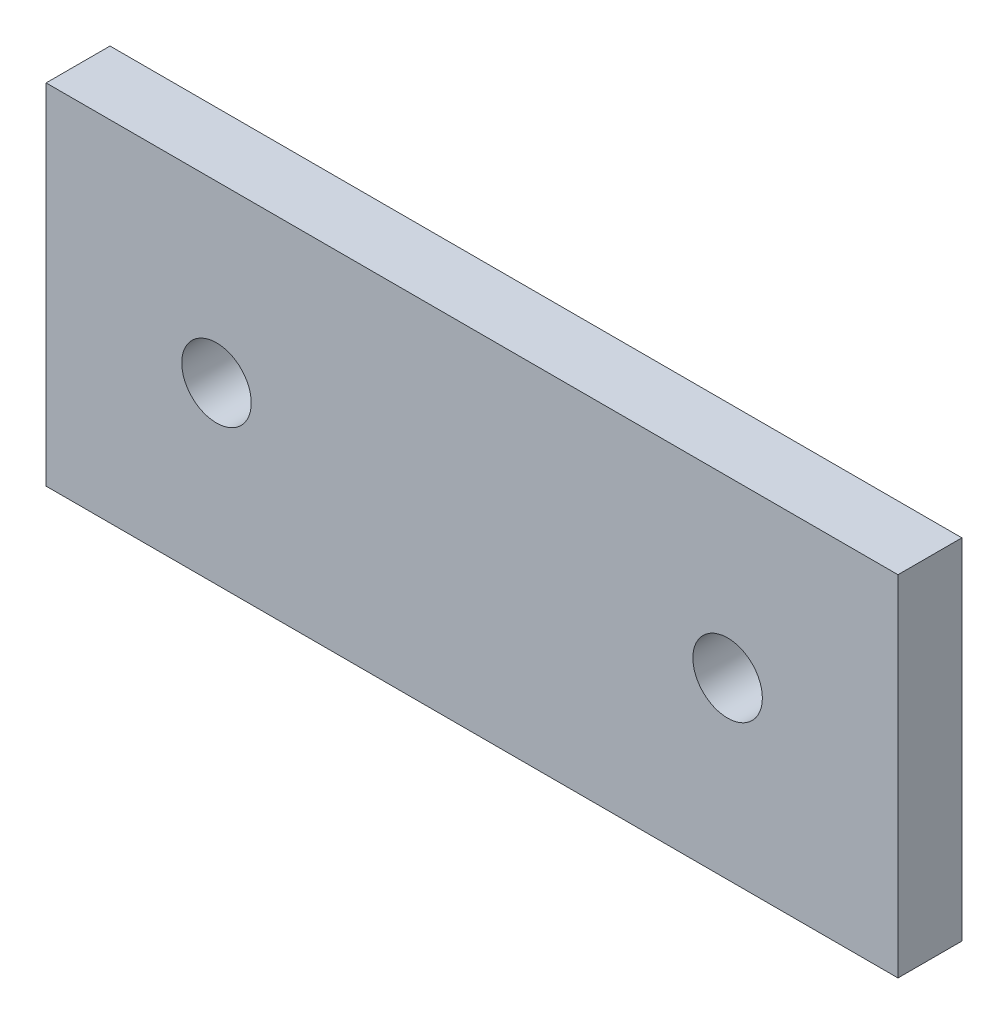
SolidWorks part; units mm, degrees
ref_plane "Front Plane" through (0, 0, 0) normal (0, 0, 1) x (1, 0, 0)
ref_plane "Top Plane" through (0, 0, 0) normal (0, 1, 0) x (1, 0, 0)
ref_plane "Right Plane" through (0, 0, 0) normal (1, 0, 0) x (0, 0, -1)
sketch "Sketch1" plane through (0, 0, 0) normal (0, 0, 1) x (1, 0, 0)
  line L1 (-20, 8.2) -> (20, 8.2)
  line L2 (-20, 8.2) -> (-20, -8.2)
  line L3 (-20, -8.2) -> (20, -8.2)
  line L4 (20, 8.2) -> (20, -8.2)
  line L5 (-20, 8.2) -> (20, -8.2) construction
  line L6 (-20, -8.2) -> (20, 8.2) construction
  point P0 (0, 0)
  dimension "D1" = 40
  dimension "D2" = 16.4
extrude "Boss-Extrude1" add sketch "Sketch1" against normal blind 3 contours L2 L3 L4 L1
hole_wizard "#4 Clearance Hole1" positions "Sketch2" profile "Sketch3" hole size "#4" standard "ANSI Inch"
sketch "Sketch2" plane through (0, 0, 0) normal (0, 0, 1) x (1, 0, 0)
  point P0 (-12, 0)
  point P2 (12, 0)
  point P7 (0, 0)
  dimension "D1" = 12
  dimension "D2" = 12
sketch "Sketch3" plane through (-12, 0, 0) normal (1, 0, 0) x (0, -1, 0)
  line L0 (0, 0) -> (0, 10.9806)
  line L1 (0, 10.9806) -> (1.6319, 10)
  line L2 (1.6319, 10) -> (1.6319, 0)
  line L5 (1.6319, 0) -> (0, 0)
  line L10 (0, 10.9806) -> (-1.6319, 10) construction
  line L11 (0, -6.35) -> (0, 107.95) construction
  dimension "Hole Dia." = 3.2639
  dimension "Hole Depth" = 10
  dimension "Drill Angle" = 118
equation "\"D2@Sketch2\"=\"D1@Sketch2\""
